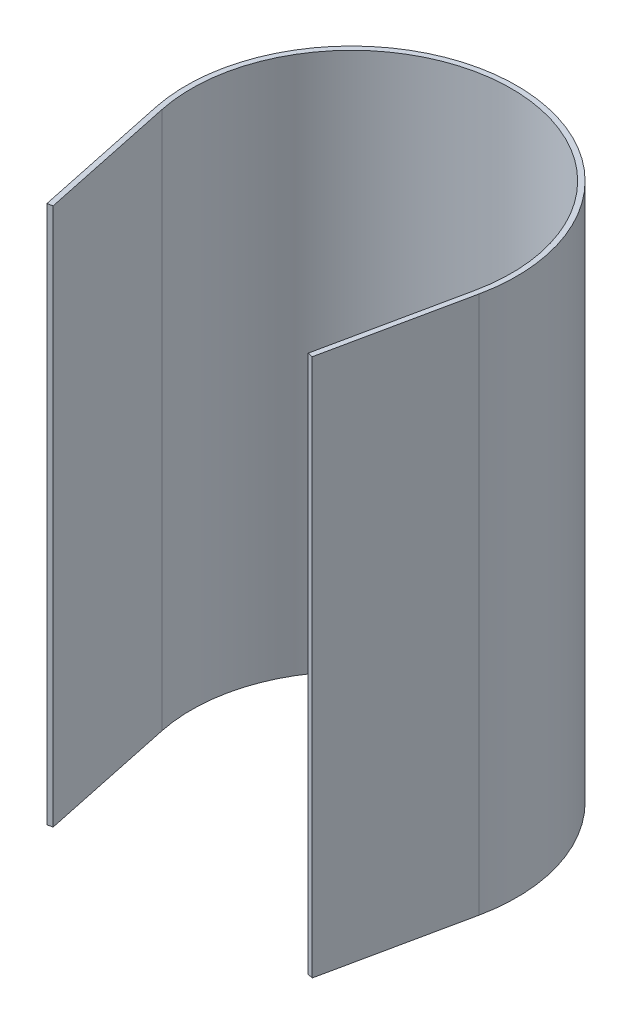
SolidWorks part; units mm, degrees
ref_plane "Front Plane" through (0, 0, 0) normal (0, 0, 1) x (1, 0, 0)
ref_plane "Top Plane" through (0, 0, 0) normal (0, 1, 0) x (1, 0, 0)
ref_plane "Right Plane" through (0, 0, 0) normal (1, 0, 0) x (0, 0, -1)
sketch "Electronics Glass Sketch" plane through (0, 0, 0) normal (0, 1, 0) x (1, 0, 0)
  line L0 (0, 0) -> (0, 609.6) construction
  line L1 (0, 0) -> (609.6, 0) construction
  line L2 (0, 0) -> (0, -1180) construction
  line L3 (0, -1180) -> (395, -1180) construction
  line L4 (616.0973, -129.693) -> (505.5487, -654.8465)
  line L5 (505.5487, -654.8465) -> (395, -1180) construction
  line L6 (485.9776, -650.7266) -> (505.5487, -654.8465)
  line L7 (0, 0) -> (609.6, 0) construction
  line L8 (0, 0) -> (596.5262, -125.5731) construction
  line L9 (596.5262, -125.5731) -> (485.9776, -650.7266)
  line L10 (0, 609.6) -> (0, 629.6) construction
  line L11 (-485.9776, -650.7266) -> (-505.5487, -654.8465)
  line L12 (-596.5262, -125.5731) -> (-485.9776, -650.7266)
  line L13 (-616.0973, -129.693) -> (-505.5487, -654.8465)
  arc A0 (616.0973, -129.693) -> (-616.0973, -129.693) centre (0, 0) ccw
  arc A1 (609.6, 0) -> (-609.6, 0) centre (0, 0) ccw
  arc A2 (596.5262, -125.5731) -> (609.6, 0) centre (0, 0) ccw
  arc A3 (-596.5262, -125.5731) -> (-609.6, 0) centre (0, 0) cw
  dimension "D1" = 20
  dimension "D2" = 1180
  dimension "D3" = 395
  dimension "D4" = 20
extrude "Electronics Glass Extrude" add sketch "Electronics Glass Sketch" along normal blind 2050
equation "\"PressureHull_InnerRadius\"= 546.1mm"
equation "\"PressureHull_OuterRadius\"= 609.6mm"
equation "\"InnerShell_InnerRadius\"= 543mm"
